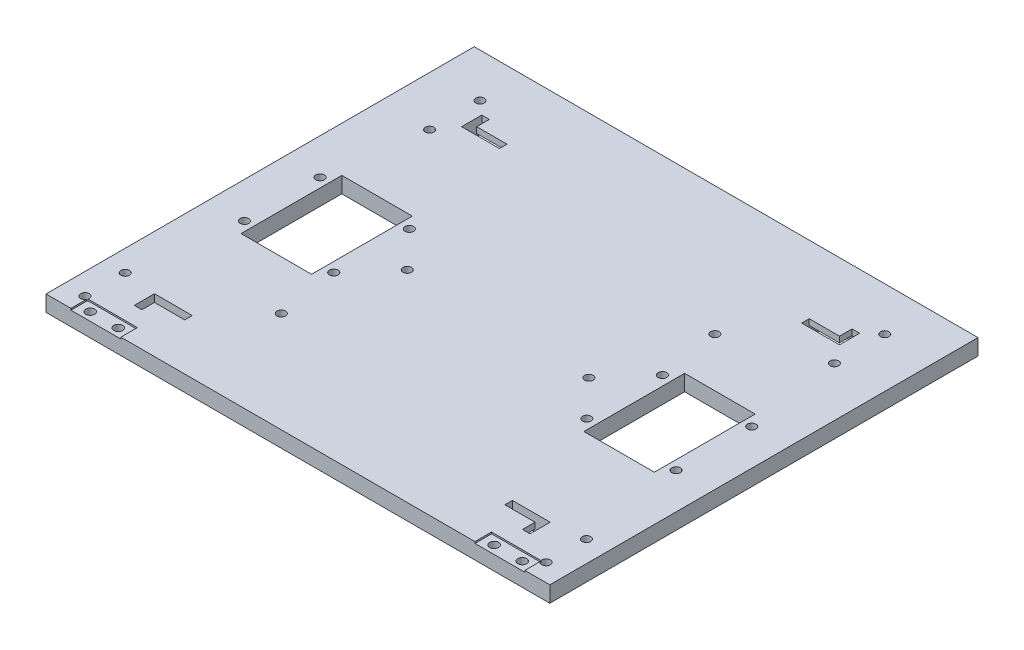
SolidWorks part; units mm, degrees
material "1023 Carbon Steel Sheet (SS)"
ref_plane "Front Plane" through (0, 0, 0) normal (0, 0, 1) x (1, 0, 0)
ref_plane "Top Plane" through (0, 0, 0) normal (0, 1, 0) x (1, 0, 0)
ref_plane "Right Plane" through (0, 0, 0) normal (1, 0, 0) x (0, 0, -1)
sketch "Sketch1" plane through (0, 0, 0) normal (0, 1, 0) x (1, 0, 0)
  line L1 (-100, -85) -> (100, -85)
  line L2 (-100, -85) -> (-100, 85)
  line L3 (-100, 85) -> (100, 85)
  line L4 (100, -85) -> (100, 85)
  line L5 (-100, -85) -> (100, 85) construction
  line L6 (-100, 85) -> (100, -85) construction
  point P0 (0, 0)
  dimension "D1" = 200
  dimension "D2" = 170
extrude "1/4\" Steel Plate" add sketch "Sketch1" along normal blind 6.35
ref_plane "Midplane" through (0, 0, 0) normal (-1, 0, 0) x (0, 0, 1)
sketch "Sketch2" plane through (0, 6.35, 0) normal (0, 1, 0) x (1, 0, 0)
  line L0 (-100, -85) -> (100, -85) construction
  line L1 (-90.094, -85) -> (-70.282, -85)
  line L2 (-90.094, -85) -> (-90.094, -78.396)
  line L3 (-90.094, -78.396) -> (-70.282, -78.396)
  line L4 (-70.282, -85) -> (-70.282, -78.396)
  line L5 (-100, 85) -> (-100, -85) construction
  dimension "D1" = 9.906
  dimension "D2" = 6.604
  dimension "D3" = 19.812
extrude "BladeHingeCut" cut sketch "Sketch2" against normal blind 0.635
hole_wizard "BladeHingeHole" positions "3DSketch2" profile "Sketch4" hole size "#8" standard "ANSI Inch" end condition through all
sketch3d "3DSketch2"
  line L0 (-90.094, 5.715, 85) -> (-70.282, 5.715, 85) construction
  line L10 (-80.188, 5.715, 78.396) -> (-80.188, 5.715, 85) construction
  line L11 (-70.282, 5.715, 78.396) -> (-90.094, 5.715, 78.396) construction
  point P0 (-74.6, 5.715, 81.698)
  point P2 (-85.776, 5.715, 81.698)
  dimension "D1" = 3.302
  dimension "D2" = 3.302
  dimension "D3" = 11.176
  dimension "D4" = 5.588
sketch "Sketch4" plane through (-74.6, 5.715, 81.698) normal (1, 0, 0) x (0, 0, 1)
  line L0 (0, 0) -> (0, 5.715)
  line L1 (0, 5.715) -> (1.778, 5.715)
  line L2 (1.778, 5.715) -> (1.778, 0)
  line L5 (1.778, 0) -> (0, 0)
  line L11 (0, -6.35) -> (0, 107.95) construction
  dimension "Thru Hole Dia." = 3.556
  dimension "Thru Hole Depth" = 5.715
sketch "Sketch5" plane through (0, 0, 0) normal (0, -1, 0) x (1, 0, 0)
  line L1 (-88.301, 79.173) -> (-83.251, 79.173)
  line L2 (-88.301, 79.173) -> (-88.301, 84.223)
  line L3 (-88.301, 84.223) -> (-83.251, 84.223)
  line L4 (-83.251, 79.173) -> (-83.251, 84.223)
  line L5 (-88.301, 79.173) -> (-83.251, 84.223) construction
  line L6 (-88.301, 84.223) -> (-83.251, 79.173) construction
  line L7 (-72.075, 79.173) -> (-77.125, 79.173)
  line L8 (-72.075, 79.173) -> (-72.075, 84.223)
  line L9 (-72.075, 84.223) -> (-77.125, 84.223)
  line L10 (-77.125, 79.173) -> (-77.125, 84.223)
  line L11 (-72.075, 79.173) -> (-77.125, 84.223) construction
  line L12 (-72.075, 84.223) -> (-77.125, 79.173) construction
  point P0 (-85.776, 81.698)
  point P6 (-74.6, 81.698)
  dimension "D1" = 5.05
  dimension "D2" = 5.05
  dimension "D3" = 5.05
  dimension "D4" = 5.05
extrude "BladeNutCut" cut sketch "Sketch5" against normal blind 2
mirror "BladeHingeMirror" about plane through (0, 0, 0) normal (-1, 0, 0) of "BladeNutCut", "BladeHingeHole", "BladeHingeCut"
sketch "Sketch6" plane through (0, 0, 0) normal (0, -1, 0) x (-1, 0, 0)
  line L0 (81.0505, -27.4233) -> (81.0505, 16.3767) construction
  line L1 (82.0505, 14.4767) -> (54.0505, 14.4767)
  line L2 (82.0505, 14.4767) -> (82.0505, -25.5233)
  line L3 (82.0505, -25.5233) -> (54.0505, -25.5233)
  line L4 (54.0505, 14.4767) -> (54.0505, -25.5233)
  line L5 (61.0505, 16.3767) -> (61.0505, -27.4233) construction
  point P6 (82.0505, -5.5233)
  dimension "D1" = 1
  dimension "D2" = 20
  dimension "D3" = 7
  dimension "D4" = 20
extrude "Cut-Extrude1" cut sketch "Sketch6" against normal up to surface (6.35 mm away) up to face at (0, 6.35, 54.4653)
sketch "Sketch7" plane through (0, 0, 0) normal (0, -1, 0) x (-1, 0, 0)
  line L0 (54.0505, -25.5233) -> (82.0505, -25.5233) construction
  line L1 (83.0505, -30.5233) -> (53.0505, -30.5233)
  line L2 (83.0505, -30.5233) -> (83.0505, -40.5233)
  line L3 (83.0505, -40.5233) -> (53.0505, -40.5233)
  line L4 (53.0505, -30.5233) -> (53.0505, -40.5233)
  line L5 (83.0505, 19.4767) -> (53.0505, 19.4767)
  line L6 (83.0505, 19.4767) -> (83.0505, 29.4767)
  line L7 (83.0505, 29.4767) -> (53.0505, 29.4767)
  line L8 (53.0505, 19.4767) -> (53.0505, 29.4767)
  line L9 (32.0505, -25.5233) -> (22.0505, -25.5233)
  line L10 (32.0505, -25.5233) -> (32.0505, 14.4767)
  line L11 (32.0505, 14.4767) -> (22.0505, 14.4767)
  line L12 (22.0505, -25.5233) -> (22.0505, 14.4767)
  line L14 (15, -30.5233) -> (-15, -30.5233)
  line L15 (15, -30.5233) -> (15, -20.5233)
  line L16 (15, -20.5233) -> (-15, -20.5233)
  line L17 (82.0505, -25.5233) -> (82.0505, 14.4767) construction
  line L18 (82.0505, 14.4767) -> (54.0505, 14.4767) construction
  line L19 (54.0505, 14.4767) -> (54.0505, -25.5233) construction
  line L20 (-15, -30.5233) -> (-15, -20.5233)
  line L21 (15, -10.5233) -> (-15, -10.5233)
  line L22 (15, -10.5233) -> (15, -0.5233)
  line L23 (15, -0.5233) -> (-15, -0.5233)
  line L24 (-15, -10.5233) -> (-15, -0.5233)
  line L25 (15, 9.4767) -> (-15, 9.4767)
  line L26 (15, 9.4767) -> (15, 19.4767)
  line L27 (15, 19.4767) -> (-15, 19.4767)
  line L28 (-15, 9.4767) -> (-15, 19.4767)
  line L29 (49.0505, -80.5233) -> (39.0505, -80.5233)
  line L30 (49.0505, -80.5233) -> (49.0505, -50.5233)
  line L31 (49.0505, -50.5233) -> (39.0505, -50.5233)
  line L32 (39.0505, -80.5233) -> (39.0505, -50.5233)
  line L33 (20, -70.5233) -> (-20, -70.5233)
  line L34 (20, -70.5233) -> (20, -60.5233)
  line L35 (20, -60.5233) -> (-20, -60.5233)
  line L36 (-20, -70.5233) -> (-20, -60.5233)
  line L37 (-100, 85) -> (100, 85) construction
  line L38 (39.0505, 39.4767) -> (49.0505, 39.4767)
  line L39 (39.0505, 39.4767) -> (39.0505, 69.4767)
  line L40 (39.0505, 69.4767) -> (49.0505, 69.4767)
  line L41 (49.0505, 39.4767) -> (49.0505, 69.4767)
  line L42 (20, 49.4767) -> (-20, 49.4767)
  line L43 (20, 49.4767) -> (20, 59.4767)
  line L44 (20, 59.4767) -> (-20, 59.4767)
  line L45 (-20, 49.4767) -> (-20, 59.4767)
  point P42 (15, -5.5233)
  point P43 (22.0505, -5.5233)
  point P52 (0, -60.5233)
  point P53 (0, -30.5233)
  point P54 (0, 49.4767)
  point P55 (20, 54.4767)
  point P56 (39.0505, 54.4767)
  point P57 (20, -65.5233)
  point P58 (39.0505, -65.5233)
  point P60 (0, 85)
  point P61 (0, -0.5233)
  dimension "D1" = 5
  dimension "D2" = 30
  dimension "D3" = 10
  dimension "D4" = 1
  dimension "D5" = 5
  dimension "D6" = 1
  dimension "D7" = 10
  dimension "D8" = 30
  dimension "D9" = 40
  dimension "D10" = 10
  dimension "D11" = 22
  dimension "D12" = 30
  dimension "D13" = 10
  dimension "D14" = 10
  dimension "D15" = 10
  dimension "D16" = 10
  dimension "D17" = 5
  dimension "D18" = 40
  dimension "D19" = 10
  dimension "D20" = 30
  dimension "D21" = 25
  dimension "D22" = 10
  dimension "D23" = 30
  dimension "D24" = 25
  dimension "D25" = 10
  dimension "D26" = 40
other "AlignGroup1"
extrude "Cut-Extrude2" cut sketch "Sketch7" against normal blind 5 contours L30 L29 L32 L31 | L34 L33 L36 L35 | L15 L14 L20 L16 | L22 L21 L24 L23 | L10 L9 L12 L11 | L2 L1 L4 L3 | L6 L5 L8 L7 | L39 L38 L41 L40 | L43 L42 L45 L44 | L26 L25 L28 L27
sketch "Sketch8" plane through (0, 6.35, 0) normal (0, 1, 0) x (1, 0, 0)
  line L0 (-83.5459, -55) -> (-83.5459, -85) construction
  line L1 (-78.5459, -63.396) -> (-63.5459, -63.396)
  line L2 (-78.5459, -63.396) -> (-78.5459, -73.396)
  line L3 (-78.5459, -73.396) -> (-63.5459, -73.396)
  line L4 (-63.5459, -63.396) -> (-63.5459, -73.396)
  line L5 (-70.282, -78.396) -> (-90.094, -78.396) construction
  dimension "D1" = 10
  dimension "D2" = 15
  dimension "D3" = 5
  dimension "D4" = 5
extrude "Cut-Extrude3" cut sketch "Sketch8" along normal blind 4 from surface at -6.35 starting at face at (0, 0, -54.4767)
sketch "Sketch9" plane through (0, 4, 0) normal (0, -1, 0) x (1, 0, 0)
  line L0 (-78.5459, 63.396) -> (-63.5459, 63.396)
  line L9 (-78.5459, 63.396) -> (-78.5459, 71.396)
  line L10 (-78.5459, 73.396) -> (-78.5459, 63.396) construction
  line L11 (-78.5459, 71.396) -> (-75.5459, 71.396)
  line L12 (-75.5459, 71.396) -> (-75.5459, 66.396)
  line L13 (-75.5459, 66.396) -> (-63.5459, 66.396)
  line L14 (-63.5459, 63.396) -> (-63.5459, 73.396) construction
  line L15 (-63.5459, 66.396) -> (-63.5459, 63.396)
  dimension "D1" = 8
  dimension "D2" = 3
  dimension "D3" = 3
extrude "Cut-Extrude4" cut sketch "Sketch9" against normal up to surface (2.35 mm away) contours L13 L15 L0 L9 L11 L12 up to face at (-68.0505, 6.35, 5.5233)
sketch "Sketch10" plane through (0, 0, 0) normal (0, -1, 0) x (-1, 0, 0)
  line L1 (75, 65) -> (60, 65)
  line L2 (75, 65) -> (75, 55)
  line L3 (75, 55) -> (60, 55)
  line L4 (60, 65) -> (60, 55)
  line L6 (100, 85) -> (100, -85) construction
  line L7 (-100, 85) -> (100, 85) construction
  dimension "D1" = 10
  dimension "D2" = 15
  dimension "D3" = 25
  dimension "D4" = 20
extrude "Cut-Extrude5" cut sketch "Sketch10" against normal blind 4
sketch "Sketch11" plane through (0, 4, 0) normal (0, -1, 0) x (1, 0, 0)
  line L0 (-60, -55) -> (-75, -55)
  line L1 (-75, -55) -> (-75, -63)
  line L2 (-75, -55) -> (-75, -65) construction
  line L3 (-75, -63) -> (-72, -63)
  line L4 (-72, -63) -> (-72, -58)
  line L5 (-72, -58) -> (-60, -58)
  line L6 (-60, -65) -> (-60, -55) construction
  line L7 (-60, -58) -> (-60, -55)
  dimension "D1" = 3
  dimension "D2" = 3
  dimension "D3" = 8
extrude "Cut-Extrude6" cut sketch "Sketch11" against normal up to next
mirror "Mirror2" about plane through (0, 0, 0) normal (-1, 0, 0) of "Cut-Extrude6", "Cut-Extrude5", "Cut-Extrude4", "Cut-Extrude3", "Cut-Extrude2", "Cut-Extrude1"
hole_wizard "CSK for M3 Flat Head Machine Screw1" positions "Sketch12" profile "Sketch13" countersink size "M3" standard "ANSI Metric"
sketch "Sketch12" plane through (0, 0, 0) normal (0, -1, 0) x (-1, 0, 0)
  point P0 (-91.5503, -78)
  point P2 (-91.5503, -62)
  point P4 (-80.3371, 47.6378)
  point P7 (-80.3371, 67.6378)
  point P10 (-36.5755, -6.0466)
  point P13 (-46.5755, 33.9534)
  point P16 (36.5755, -5)
  point P19 (46.5755, -45)
  point P22 (91.5459, -62)
  point P25 (91.5459, -78)
  point P28 (80.3371, 47.6378)
  point P31 (80.3371, 67.6378)
  point P39 (-85.6905, -20.5233)
  point P42 (-85.6905, 9.4767)
  point P45 (-50.2355, -20.5233)
  point P48 (-50.2355, 9.4767)
  point P51 (50.2355, -20.5233)
  point P54 (85.6905, -20.5233)
  point P57 (85.6905, 9.4767)
  point P60 (50.2355, 9.4767)
sketch "Sketch13" plane through (91.5503, 0, 78) normal (1, 0, 0) x (0, 0, -1)
  line L0 (0, 0) -> (0, 14)
  line L1 (0, 14) -> (1.7, 14)
  line L2 (1.7, 14) -> (1.7, 1.45)
  line L3 (1.7, 1.45) -> (3.15, 0)
  line L5 (3.15, 0) -> (0, 0)
  line L6 (-1.7, 1.45) -> (-3.15, 0) construction
  line L10 (0, 14) -> (-1.7, 14) construction
  line L11 (0, -6.35) -> (0, 107.95) construction
  dimension "Hole Dia." = 3.4
  dimension "Hole Depth" = 14
  dimension "Near C'Sink Dia." = 6.3
  dimension "Near C'Sink Angle" = 90
  dimension "Drill Angle" = 180
